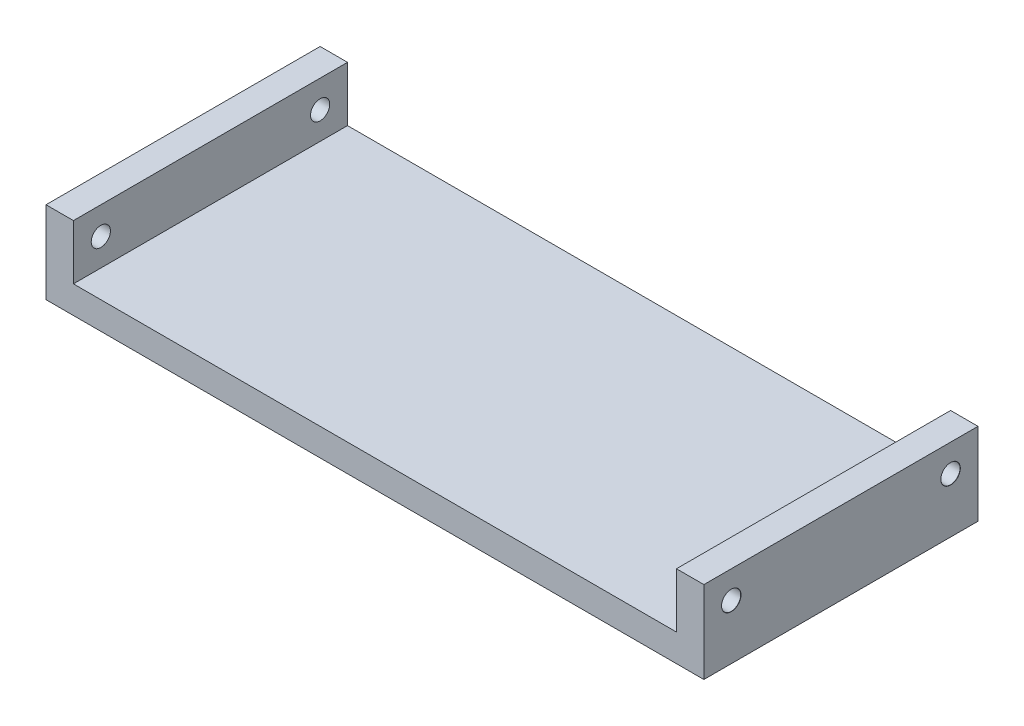
SolidWorks part; units mm, degrees
ref_plane "Front Plane" through (0, 0, 0) normal (0, 0, 1) x (1, 0, 0)
ref_plane "Top Plane" through (0, 0, 0) normal (0, 1, 0) x (1, 0, 0)
ref_plane "Right Plane" through (0, 0, 0) normal (1, 0, 0) x (0, 0, -1)
sketch "Sketch1" plane through (0, 0, 0) normal (0, 1, 0) x (1, 0, 0)
  line L1 (60, -25) -> (-60, -25)
  line L2 (60, -25) -> (60, 25)
  line L3 (60, 25) -> (-60, 25)
  line L4 (-60, -25) -> (-60, 25)
  line L5 (60, -25) -> (-60, 25) construction
  line L6 (60, 25) -> (-60, -25) construction
  point P0 (0, 0)
  dimension "D1" = 120
  dimension "50" = 50
extrude "Boss-Extrude1" add sketch "Sketch1" along normal blind 5
sketch "Sketch2" plane through (0, 5, 0) normal (0, 1, 0) x (1, 0, 0)
  line L0 (-60, -25) -> (60, -25) construction
  line L1 (-60, 25) -> (-55, 25)
  line L2 (-60, 25) -> (-60, -25)
  line L3 (-60, -25) -> (-55, -25)
  line L4 (-55, 25) -> (-55, -25)
  line L6 (60, 25) -> (55, 25)
  line L7 (60, 25) -> (60, -25)
  line L8 (60, -25) -> (55, -25)
  line L9 (55, 25) -> (55, -25)
  dimension "D1" = 5
  dimension "D2" = 5
extrude "Boss-Extrude2" add sketch "Sketch2" along normal blind 10
hole_wizard "Ø3.5 (3.5) Diameter Hole1" positions "Sketch5" profile "Sketch4" hole size "Ø3.5" standard "ISO" end condition through all
sketch "Sketch5" plane through (60, 0, 0) normal (1, 0, 0) x (0, 0, -1)
  line L0 (-25, 15) -> (-25, 0) construction
  line L1 (-25, 15) -> (25, 15) construction
  line L2 (25, 15) -> (25, 0) construction
  point P0 (-20, 10)
  point P2 (20, 10)
  point P9 (0, 0)
  dimension "D1" = 5
  dimension "D2" = 5
  dimension "D3" = 5
sketch "Sketch4" plane through (60, 10, 20) normal (0, 1, 0) x (0, 0, -1)
  line L0 (0, 0) -> (0, 120)
  line L1 (0, 120) -> (1.75, 120)
  line L2 (1.75, 120) -> (1.75, 0.025)
  line L3 (1.75, 0.025) -> (1.775, 0)
  line L5 (1.775, 0) -> (0, 0)
  line L6 (-1.75, 0.025) -> (-1.775, 0) construction
  line L11 (0, -6.35) -> (0, 107.95) construction
  dimension "Thru Hole Dia." = 3.5
  dimension "Thru Hole Depth" = 120
  dimension "Near C'Sink Dia." = 3.55
  dimension "Near C'Sink Angle" = 90
